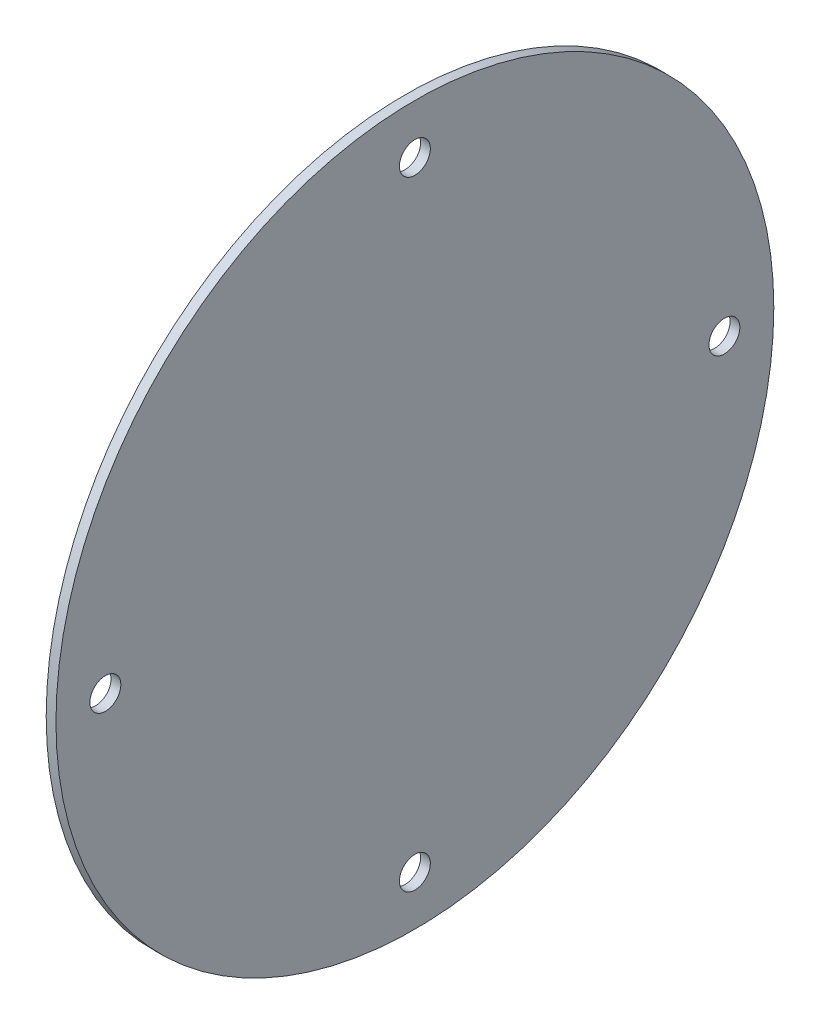
SolidWorks part; units mm, degrees
ref_plane "Front Plane" through (0, 0, 0) normal (1, 0, 0) x (0, 1, 0)
ref_plane "Top Plane" through (0, 0, 0) normal (0, 0, 1) x (0, 1, 0)
ref_plane "Right Plane" through (0, 0, 0) normal (0, 1, 0) x (-1, 0, 0)
sketch "Sketch1" plane through (0, 0, 0) normal (1, 0, 0) x (0, 1, 0)
  circle A0 centre (0, 0) radius 73.787
  dimension "D1" = 147.574
extrude "Boss-Extrude1" add sketch "Sketch1" along normal blind 2.0066
sketch "Sketch2" plane through (2.0066, 0, 0) normal (1, 0, 0) x (0, 0, -1)
  line L0 (-73.787, 0) -> (-63.627, 0)
  line L1 (-73.787, 0) -> (-60.452, 0)
  circle A0 centre (0, 0) radius 73.787 construction
  circle A1 centre (-63.627, 0) radius 3.175
  dimension "D2" = 6.35
  dimension "D1" = 10.16
extrude "Cut-Extrude1" cut sketch "Sketch2" against normal through all contours A1
pattern_circular "CirPattern1" count 4 over 360 about axis through (0, 0, 0) along (1, 0, 0) of "Cut-Extrude1"
